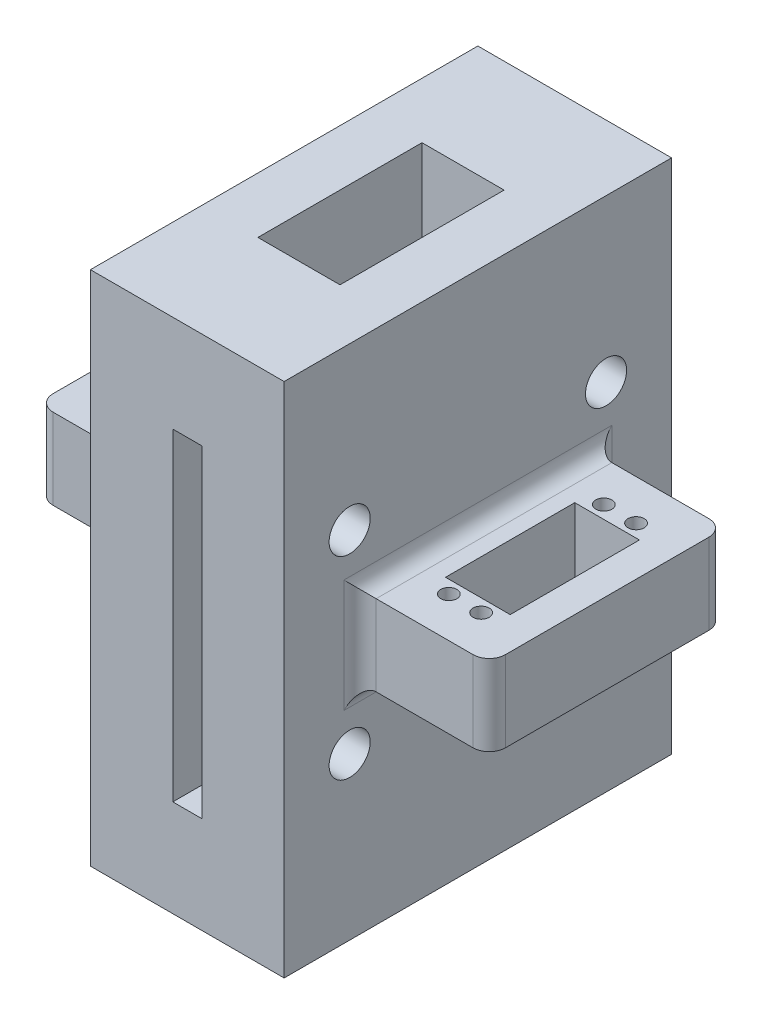
SolidWorks part; units mm, degrees
ref_plane "Front Plane" through (0, 0, 0) normal (0, 0, 1) x (1, 0, 0)
ref_plane "Top Plane" through (0, 0, 0) normal (0, 1, 0) x (1, 0, 0)
ref_plane "Right Plane" through (0, 0, 0) normal (1, 0, 0) x (0, 0, -1)
sketch "Sketch1" plane through (0, 0, 0) normal (0, 1, 0) x (1, 0, 0)
  line L1 (-30, -60) -> (30, -60)
  line L2 (-30, -60) -> (-30, 60)
  line L3 (-30, 60) -> (30, 60)
  line L4 (30, -60) -> (30, 60)
  line L5 (-30, -60) -> (30, 60) construction
  line L6 (-30, 60) -> (30, -60) construction
  point P0 (0, 0)
  dimension "D1" = 60
  dimension "D2" = 120
extrude "Boss-Extrude1" add sketch "Sketch1" along normal mid plane 160
fillet "Fillet1" [suppressed] radius 30
sketch "Sketch3" plane through (0, 0, 0) normal (0, 1, 0) x (0, 0, -1)
  line L1 (-25.415, -12.715) -> (25.415, -12.715)
  line L2 (-25.415, -12.715) -> (-25.415, 12.715)
  line L3 (-25.415, 12.715) -> (25.415, 12.715)
  line L4 (25.415, -12.715) -> (25.415, 12.715)
  point P4 (0, 12.715)
  point P7 (25.415, 0)
  dimension "D1" = 50.83
  dimension "D2" = 25.43
extrude "Cut-Extrude2" cut sketch "Sketch3" against normal up to surface and the other way up to surface up to face at (0, -80, 0) other way up to face at (0, 80, 0)
sketch "Sketch5" plane through (0, 0, 0) normal (0, 0, 1) x (1, 0, 0)
  line L1 (-4.4837, -50) -> (4.4838, -50)
  line L2 (-4.4837, -50) -> (-4.4837, 50)
  line L3 (-4.4837, 50) -> (4.4838, 50)
  line L4 (4.4838, -50) -> (4.4838, 50)
  line L5 (-4.4837, -50) -> (4.4838, 50) construction
  line L6 (-4.4837, 50) -> (4.4838, -50) construction
  point P0 (0, 0)
  dimension "D1" = 8.9675
  dimension "D2" = 100
extrude "Cut-Extrude3" cut sketch "Sketch5" along normal up to surface and the other way up to surface up to face at (0, 0, 60) other way up to face at (0, 0, -60)
sketch "Sketch6" plane through (0, 0, 0) normal (1, 0, 0) x (0, 0, -1)
  line L0 (-25.415, -50) -> (-25.415, 50) construction
  line L1 (0, 0) -> (-60, 0) construction
  line L2 (0, 0) -> (0, 80) construction
  line L3 (-25.415, 80) -> (25.415, 80) construction
  line L4 (-60, -50) -> (-60, 50) construction
  circle A0 centre (-39.705, -30) radius 6.365
  circle A1 centre (-39.705, 30) radius 6.365
  circle A2 centre (39.705, -30) radius 6.365
  circle A3 centre (39.705, 30) radius 6.365
  dimension "D2" = 12.73
  dimension "D1" = 14.29
  dimension "D3" = 30
extrude "Cut-Extrude4" cut sketch "Sketch6" along normal up to surface and the other way up to surface up to face at (30, 0, 0) other way up to face at (-30, 0, 0)
sketch "Sketch7" plane through (0, 0, 0) normal (0, 1, 0) x (1, 0, 0)
  line L0 (-30, 60) -> (-30, -60) construction
  line L1 (-30, -36.5) -> (-70.03, -36.5)
  line L2 (-30, -36.5) -> (-30, 36.5)
  line L3 (-30, 36.5) -> (-70.03, 36.5)
  line L4 (-70.03, -36.5) -> (-70.03, 36.5)
  line L5 (-50.015, -36.5) -> (-50.015, 36.5) construction
  line L6 (-60.03, -20.015) -> (-40, -20.015)
  line L7 (-60.03, -20.015) -> (-60.03, 20.015)
  line L8 (-60.03, 20.015) -> (-40, 20.015)
  line L9 (-40, -20.015) -> (-40, 20.015)
  line L10 (-60.03, -20.015) -> (-40, 20.015) construction
  line L11 (-60.03, 20.015) -> (-40, -20.015) construction
  line L12 (-30, 0) -> (-70.03, 0) construction
  circle A0 centre (-55.015, 24) radius 2.5
  circle A1 centre (-45.015, 24) radius 2.5
  circle A2 centre (-55.015, -24) radius 2.5
  circle A6 centre (-45.015, -24) radius 2.5
  point P6 (-30, 0)
  point P9 (-50.015, 0)
  point P15 (-50.015, 36.5)
  point P24 (-50.015, 0)
  point P30 (-50.015, 0)
  dimension "D4" = 5
  dimension "D1" = 40.03
  dimension "D2" = 20.03
  dimension "D3" = 10
  dimension "D5" = 10
  dimension "D6" = 48
  dimension "D7" = 12.5
extrude "Boss-Extrude2" add sketch "Sketch7" along normal mid plane 25
mirror "Mirror2" about plane through (0, 0, 0) normal (1, 0, 0) of "Boss-Extrude2"
fillet "Fillet2" radius 5 12 edges at (-70.03, 0, 36.5) (-70.03, 0, -36.5) (-30, -12.5, 0) (-30, 0, 36.5) (-30, 12.5, 0) (-30, 0, -36.5) (70.03, 0, 36.5) (70.03, 0, -36.5) (30, 0, -36.5) (30, 12.5, 0) (30, 0, 36.5) (30, -12.5, 0)
